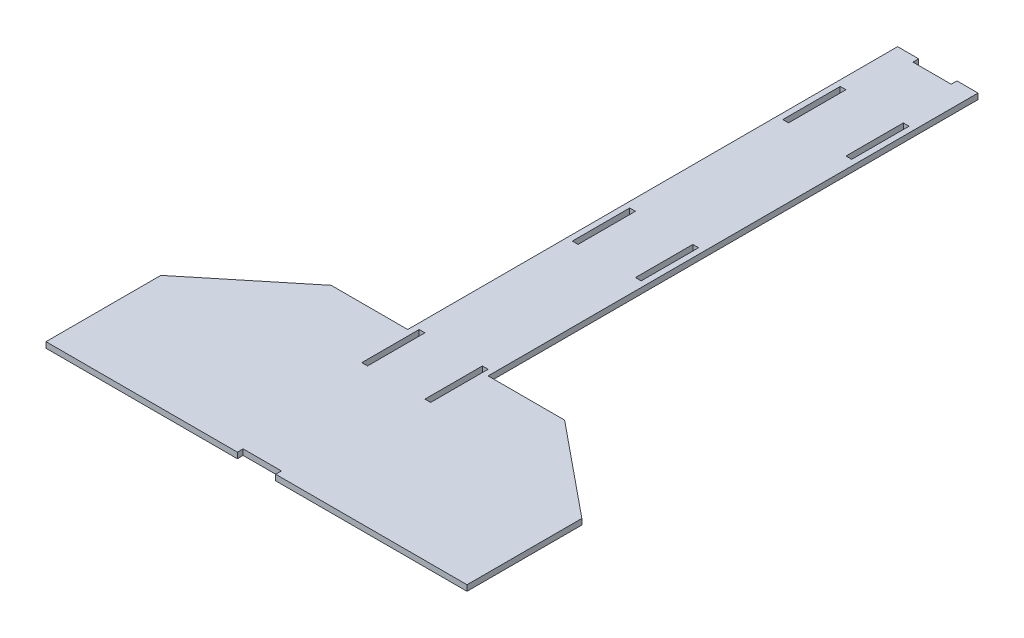
SolidWorks part; units mm, degrees
material "ABS"
ref_plane "Front Plane" through (0, 0, 0) normal (0, 0, 1) x (1, 0, 0)
ref_plane "Top Plane" through (0, 0, 0) normal (0, 1, 0) x (1, 0, 0)
ref_plane "Right Plane" through (0, 0, 0) normal (1, 0, 0) x (0, 0, -1)
sketch "Sketch1" plane through (0, 0, 0) normal (0, 1, 0) x (1, 0, 0)
  line L1 (0, 0) -> (11, 0)
  line L2 (0, 100) -> (0, 356)
  line L3 (0, 356) -> (11, 356)
  line L4 (42, 100) -> (42, 356)
  line L6 (11, 356) -> (11, 353)
  line L7 (11, 353) -> (31, 353)
  line L8 (31, 356) -> (31, 353)
  line L10 (11, 0) -> (11, 3)
  line L11 (11, 3) -> (31, 3)
  line L12 (31, 0) -> (31, 3)
  line L13 (31, 356) -> (42, 356)
  line L18 (21, 3) -> (21, 43.1488) construction
  line L19 (36, 103) -> (39, 103)
  line L20 (36, 103) -> (36, 73)
  line L21 (36, 73) -> (39, 73)
  line L22 (39, 103) -> (39, 73)
  line L23 (36, 213) -> (39, 213)
  line L24 (36, 213) -> (36, 183)
  line L25 (36, 183) -> (39, 183)
  line L26 (39, 213) -> (39, 183)
  line L27 (36, 323) -> (39, 323)
  line L28 (36, 323) -> (36, 293)
  line L29 (36, 293) -> (39, 293)
  line L30 (39, 323) -> (39, 293)
  line L31 (-89, 0) -> (-89, 60)
  line L32 (-89, 60) -> (-40, 100)
  line L33 (11, 0) -> (-89, 0)
  line L34 (-40, 100) -> (0, 100)
  line L35 (6, 73) -> (3, 73)
  line L36 (6, 103) -> (6, 73)
  line L37 (3, 103) -> (3, 73)
  line L38 (6, 103) -> (3, 103)
  line L39 (6, 183) -> (3, 183)
  line L40 (6, 213) -> (6, 183)
  line L41 (3, 213) -> (3, 183)
  line L42 (6, 213) -> (3, 213)
  line L43 (6, 293) -> (3, 293)
  line L44 (3, 323) -> (3, 293)
  line L45 (6, 323) -> (6, 293)
  line L46 (6, 323) -> (3, 323)
  line L48 (31, 0) -> (131, 0)
  line L49 (131, 0) -> (131, 60)
  line L50 (131, 60) -> (82, 100)
  line L51 (82, 100) -> (42, 100)
  dimension "D2" = 42
  dimension "D3" = 100
  dimension "D4" = 20
  dimension "D5" = 60
  dimension "D6" = 3
  dimension "D7" = 20
  dimension "D8" = 11
  dimension "D9" = 100
  dimension "D10" = 40
  dimension "D11" = 356
  dimension "D14" = 3
  dimension "D15" = 30
  dimension "D17" = 3
  dimension "D18" = 30
  dimension "D19" = 3
  dimension "D20" = 3
  dimension "D21" = 80
  dimension "D22" = 30
  dimension "D23" = 3
  dimension "D24" = 3
  dimension "D25" = 80
extrude "Boss-Extrude1" add sketch "Sketch1" along normal blind 3
